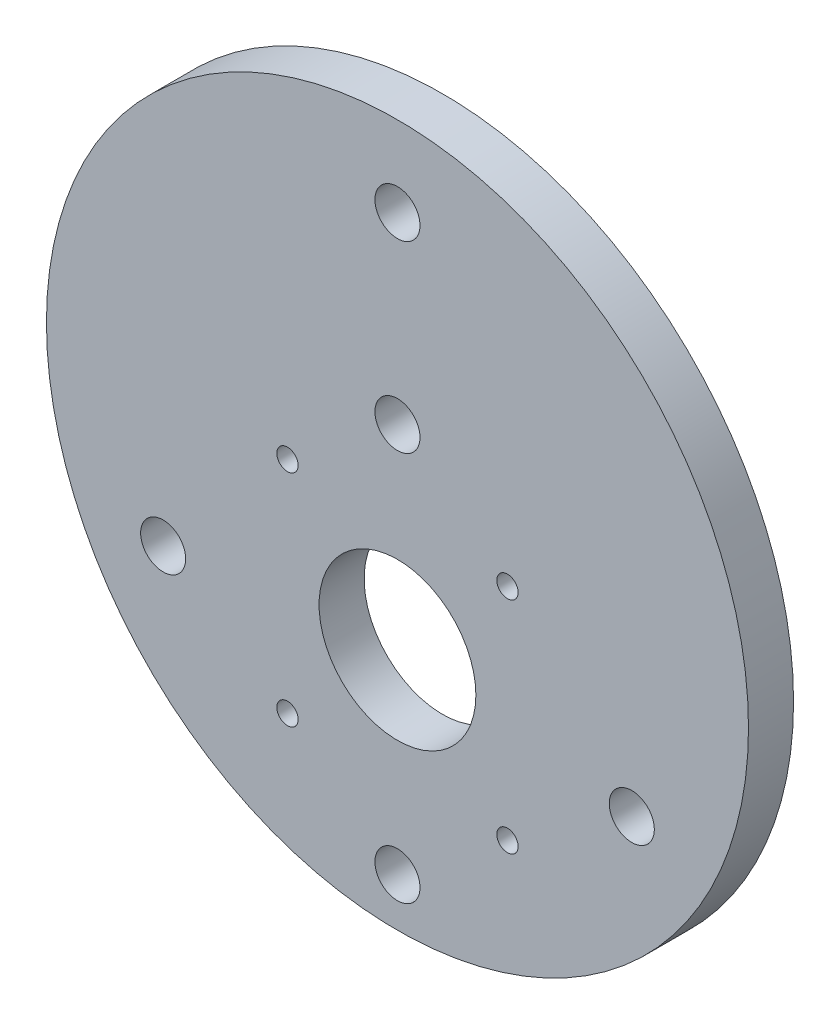
SolidWorks part; units mm, degrees
ref_plane "Front Plane" through (0, 0, 0) normal (0, 0, 1) x (1, 0, 0)
ref_plane "Top Plane" through (0, 0, 0) normal (0, 1, 0) x (1, 0, 0)
ref_plane "Right Plane" through (0, 0, 0) normal (1, 0, 0) x (0, 0, -1)
sketch "Sketch1" plane through (0, 0, 0) normal (0, 0, 1) x (1, 0, 0)
  circle A0 centre (0, 0) radius 49.4665
  dimension "D1" = 98.933
extrude "Boss-Extrude1" add sketch "Sketch1" along normal blind 6.35
sketch "Sketch2" plane through (0, 0, 6.35) normal (0, 0, 1) x (1, 0, 0)
  line L0 (-15.5, -30.74) -> (15.5, 0.26) construction
  line L1 (-15.5, 0.26) -> (15.5, 0.26)
  line L2 (-15.5, 0.26) -> (-15.5, -30.74)
  line L3 (-15.5, -30.74) -> (15.5, -30.74)
  line L4 (15.5, 0.26) -> (15.5, -30.74)
  point P4 (0, -15.24)
  point P5 (0, 0.26)
  dimension "D1" = 31
  dimension "D2" = 31
  dimension "D3" = 15.24
hole_wizard "Ø3.0mm Dowel Hole1" positions "Sketch3" profile "Sketch4" hole size "Ø3.0" standard "ANSI Metric" end condition through all
sketch "Sketch3" plane through (0, 0, 6.35) normal (0, 0, 1) x (1, 0, 0)
  point P0 (15.5, 0.26)
  point P3 (-15.5, 0.26)
  point P6 (-15.5, -30.74)
  point P9 (15.5, -30.74)
sketch "Sketch4" plane through (15.5, 0.26, 6.35) normal (1, 0, 0) x (0, -1, 0)
  line L0 (0, 0) -> (0, 6.35)
  line L1 (0, 6.35) -> (1.5, 6.35)
  line L2 (1.5, 6.35) -> (1.5, 0)
  line L5 (1.5, 0) -> (0, 0)
  line L11 (0, -6.35) -> (0, 107.95) construction
  dimension "Thru Hole Dia." = 3
  dimension "Thru Hole Depth" = 6.35
sketch "Sketch5" plane through (0, 0, 6.35) normal (0, 0, 1) x (1, 0, 0)
  line L0 (-15.5, -30.74) -> (15.5, 0.26) construction
  line L1 (-21.209, 5.969) -> (21.209, 5.969)
  line L2 (-21.209, 5.969) -> (-21.209, -36.449)
  line L3 (-21.209, -36.449) -> (21.209, -36.449)
  line L4 (21.209, 5.969) -> (21.209, -36.449)
  line L5 (-21.209, 5.969) -> (21.209, -36.449) construction
  line L6 (-21.209, -36.449) -> (21.209, 5.969) construction
  circle A0 centre (0, -42.672) radius 3.175
  circle A1 centre (0, 12.26) radius 3.175
  point P0 (0, -15.24)
  point P7 (0, -15.24)
  dimension "D3" = 6.35
  dimension "D5" = 6.35
  dimension "D1" = 42.418
  dimension "D2" = 27.5
  dimension "D4" = 42.418
  dimension "D6" = 27.432
extrude "Cut-Extrude1" cut sketch "Sketch5" against normal through all contours A0 | A1
sketch "Sketch6" plane through (0, 0, 6.35) normal (0, 0, 1) x (1, 0, 0)
  line L0 (0, 38.1282) -> (-33.02, -19.0641) construction
  line L1 (-33.02, -19.0641) -> (33.02, -19.0641) construction
  line L2 (33.02, -19.0641) -> (0, 38.1282) construction
  line L3 (-33.02, -19.0641) -> (0, 0) construction
  line L4 (0, 0) -> (33.02, -19.0641) construction
  line L5 (0, 0) -> (0, 38.1282) construction
  circle A0 centre (0, 38.1282) radius 3.175
  circle A1 centre (-33.02, -19.0641) radius 3.175
  circle A2 centre (33.02, -19.0641) radius 3.175
  dimension "D1" = 6.35
  dimension "D2" = 66.04
  dimension "D3" = 60
  dimension "D4" = 60
extrude "Cut-Extrude2" cut sketch "Sketch6" against normal through all
sketch "Sketch7" plane through (0, 0, 6.35) normal (0, 0, 1) x (1, 0, 0)
  line L0 (-15.5, -30.74) -> (15.5, 0.26) construction
  circle A0 centre (0, -15.24) radius 11.049
  point P4 (0, -15.24)
  dimension "D1" = 22.098
extrude "Cut-Extrude3" cut sketch "Sketch7" against normal through all
